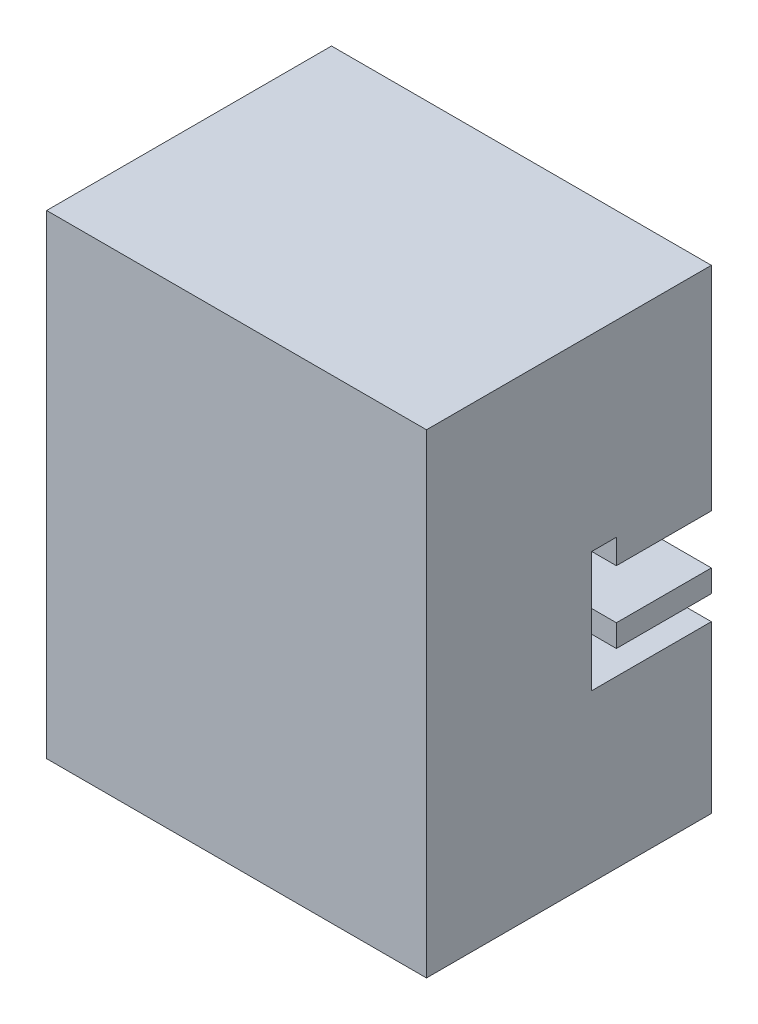
SolidWorks part; units mm, degrees
ref_plane "Front Plane" through (0, 0, 0) normal (0, 0, 1) x (1, 0, 0)
ref_plane "Top Plane" through (0, 0, 0) normal (0, 1, 0) x (1, 0, 0)
ref_plane "Right Plane" through (0, 0, 0) normal (1, 0, 0) x (0, 0, -1)
sketch "Sketch1" plane through (0, 0, 0) normal (0, 0, 1) x (1, 0, 0)
  line L1 (0, 0) -> (40, 0)
  line L2 (0, 0) -> (0, 50)
  line L3 (0, 50) -> (40, 50)
  line L4 (40, 0) -> (40, 50)
  dimension "D1" = 40
  dimension "D2" = 50
extrude "Boss-Extrude1" add sketch "Sketch1" along normal blind 30
sketch "Sketch2" plane through (0, 0, 0) normal (-1, 0, 0) x (0, 0, 1)
  line L0 (0, 25) -> (30, 25) construction
  line L1 (0, 50) -> (0, 0) construction
  line L2 (30, 50) -> (30, 0) construction
  line L3 (0, 27.6) -> (10, 27.6)
  line L4 (10, 27.6) -> (10, 30.2)
  line L5 (10, 30.2) -> (12.6, 30.2)
  line L6 (12.6, 30.2) -> (12.6, 19.8)
  line L7 (10, 19.8) -> (12.6, 19.8)
  line L8 (10, 22.4) -> (10, 19.8)
  line L9 (0, 22.4) -> (10, 22.4)
  line L10 (0, 27.6) -> (0, 22.4)
  point P12 (12.6, 25)
  dimension "D1" = 2.6
  dimension "D2" = 2.6
  dimension "D3" = 2.6
  dimension "D4" = 10
extrude "Cut-Extrude1" cut sketch "Sketch2" against normal up to next
sketch "Sketch3" plane through (0, 0, 0) normal (0, 0, -1) x (-1, 0, 0)
  line L0 (-20, 0) -> (-20, 27.6) construction
  line L1 (0, 0) -> (-40, 0) construction
  line L2 (-40, 27.6) -> (0, 27.6) construction
  line L3 (-25.05, 27.6) -> (-14.95, 27.6)
  line L4 (-14.95, 27.6) -> (-14.95, 20.05)
  line L5 (-14.95, 20.05) -> (0, 20.05)
  line L7 (0, 17.5) -> (-40, 17.5)
  line L9 (0, 20.05) -> (0, 17.5)
  line L10 (-25.05, 20.05) -> (-40, 20.05)
  line L11 (-25.05, 27.6) -> (-25.05, 20.05)
  line L12 (-40, 20.05) -> (-40, 17.5)
  point P15 (-20, 17.5)
  dimension "D1" = 7.55
  dimension "D4" = 5.05
  dimension "D5" = 2.55
extrude "Cut-Extrude2" cut sketch "Sketch3" against normal up to surface (12.6 mm away) up to face at (20, 25, 12.6)
sketch "Sketch5" plane through (0, 0, 0) normal (0, -1, 0) x (1, 0, 0)
  circle A0 centre (20, 15.8633) radius 25
  dimension "D1" = 50
